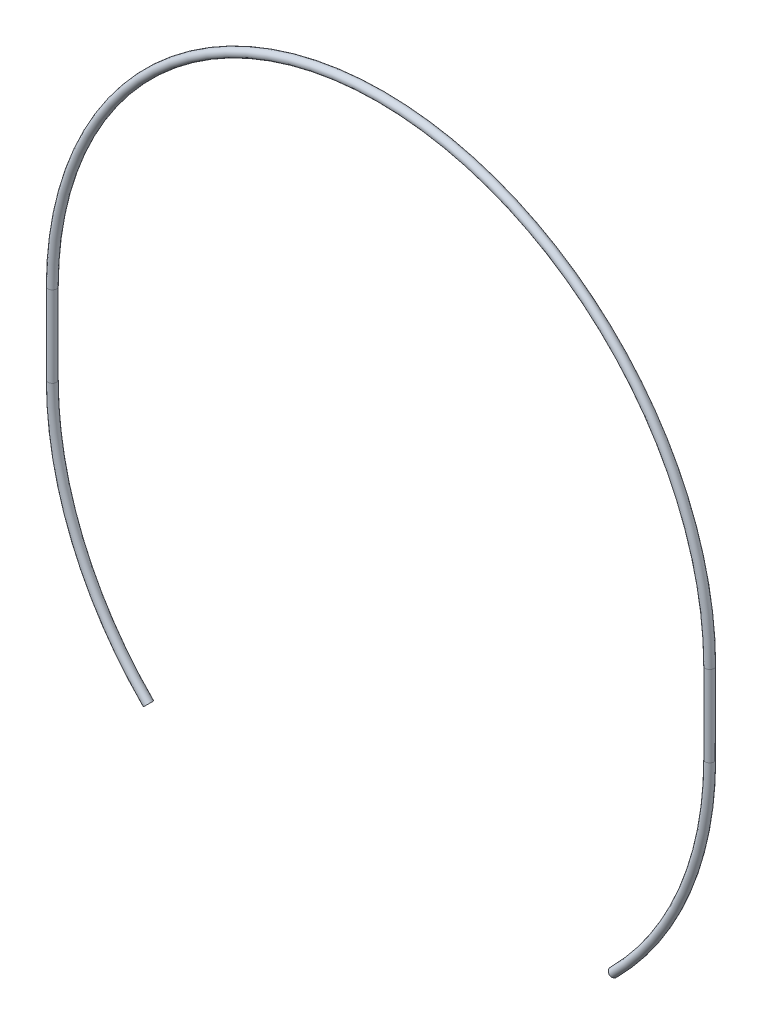
SolidWorks part; units mm, degrees
ref_plane "Front Plane" through (0, 0, 0) normal (0, 0, 1) x (1, 0, 0)
ref_plane "Top Plane" through (0, 0, 0) normal (0, 1, 0) x (1, 0, 0)
ref_plane "Right Plane" through (0, 0, 0) normal (1, 0, 0) x (0, 0, -1)
sketch "Sketch10" plane through (0, 0, 0) normal (0, 0, 1) x (1, 0, 0)
  line L0 (-195, 0) -> (195, 0) construction
  line L1 (-195, 0) -> (-195, -48)
  line L2 (195, 0) -> (195, -48)
  line L3 (-195, -48) -> (195, -48) construction
  line L4 (0, -48) -> (-137.8858, -185.8858) construction
  line L5 (0, -48) -> (137.8858, -185.8858) construction
  arc A0 (195, 0) -> (-195, 0) centre (0, 0) ccw
  arc A1 (-195, -48) -> (-137.8858, -185.8858) centre (0, -48) ccw
  arc A2 (137.8858, -185.8858) -> (195, -48) centre (0, -48) ccw
  dimension "D1" = 195
  dimension "D6" = 195
  dimension "D2" = 48
  dimension "D3" = 48
  dimension "D4" = 45
  dimension "D5" = 45
sweep "Sweep1" add path "Sketch10" circular profile diameter 5 parameters "D3"=5
